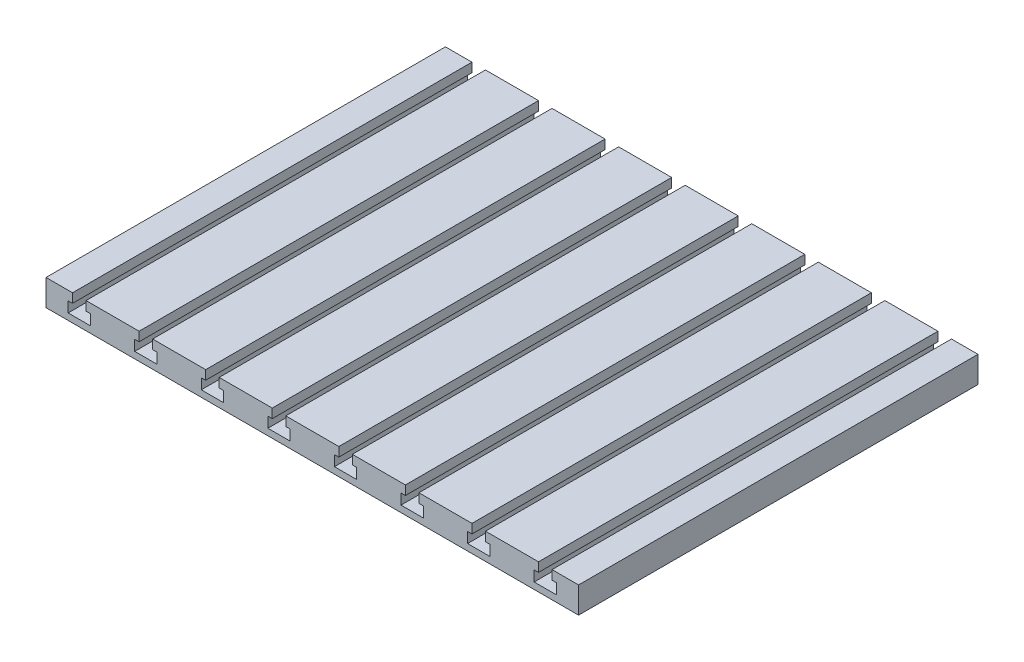
SolidWorks part; units mm, degrees
ref_plane "Front Plane" through (0, 0, 0) normal (0, 0, 1) x (1, 0, 0)
ref_plane "Top Plane" through (0, 0, 0) normal (0, 1, 0) x (1, 0, 0)
ref_plane "Right Plane" through (0, 0, 0) normal (1, 0, 0) x (0, 0, -1)
sketch "Sketch1" plane through (0, 0, 0) normal (0, 0, 1) x (1, 0, 0)
  line L0 (30.5562, 12.9794) -> (33.8963, 12.9794)
  line L1 (0, 0) -> (406.4, 0)
  line L2 (0, 0) -> (0, 19.9898)
  line L3 (0, 19.9898) -> (20.2438, 19.9898)
  line L4 (406.4, 0) -> (406.4, 19.9898)
  line L6 (20.2438, 19.9898) -> (20.2438, 12.9794)
  line L8 (30.5562, 19.9898) -> (30.5562, 12.9794)
  line L9 (16.9037, 12.9794) -> (20.2438, 12.9794)
  line L10 (16.9037, 12.9794) -> (16.9037, 4.9784)
  line L11 (16.9037, 4.9784) -> (33.8963, 4.9784)
  line L12 (33.8963, 12.9794) -> (33.8963, 4.9784)
  line L13 (25.4, 4.9784) -> (25.4, 25.0145) construction
  line L14 (71.0438, 19.9898) -> (71.0438, 12.9794)
  line L15 (67.7037, 12.9794) -> (71.0438, 12.9794)
  line L16 (67.7037, 12.9794) -> (67.7037, 4.9784)
  line L17 (67.7037, 4.9784) -> (84.6963, 4.9784)
  line L18 (84.6963, 12.9794) -> (84.6963, 4.9784)
  line L19 (81.3562, 12.9794) -> (84.6963, 12.9794)
  line L20 (81.3562, 19.9898) -> (81.3562, 12.9794)
  line L22 (121.8438, 19.9898) -> (121.8438, 12.9794)
  line L23 (118.5037, 12.9794) -> (121.8438, 12.9794)
  line L24 (118.5037, 12.9794) -> (118.5037, 4.9784)
  line L25 (118.5037, 4.9784) -> (135.4963, 4.9784)
  line L26 (135.4963, 12.9794) -> (135.4963, 4.9784)
  line L27 (132.1562, 12.9794) -> (135.4963, 12.9794)
  line L28 (132.1562, 19.9898) -> (132.1562, 12.9794)
  line L30 (172.6438, 19.9898) -> (172.6438, 12.9794)
  line L31 (169.3037, 12.9794) -> (172.6438, 12.9794)
  line L32 (169.3037, 12.9794) -> (169.3037, 4.9784)
  line L33 (169.3037, 4.9784) -> (186.2963, 4.9784)
  line L34 (186.2963, 12.9794) -> (186.2963, 4.9784)
  line L35 (182.9562, 12.9794) -> (186.2963, 12.9794)
  line L36 (182.9562, 19.9898) -> (182.9562, 12.9794)
  line L38 (223.4438, 19.9898) -> (223.4438, 12.9794)
  line L39 (220.1037, 12.9794) -> (223.4438, 12.9794)
  line L40 (220.1037, 12.9794) -> (220.1037, 4.9784)
  line L41 (220.1037, 4.9784) -> (237.0963, 4.9784)
  line L42 (237.0963, 12.9794) -> (237.0963, 4.9784)
  line L43 (233.7562, 12.9794) -> (237.0963, 12.9794)
  line L44 (233.7562, 19.9898) -> (233.7562, 12.9794)
  line L46 (274.2438, 19.9898) -> (274.2438, 12.9794)
  line L47 (270.9037, 12.9794) -> (274.2438, 12.9794)
  line L48 (270.9037, 12.9794) -> (270.9037, 4.9784)
  line L49 (270.9037, 4.9784) -> (287.8963, 4.9784)
  line L50 (287.8963, 12.9794) -> (287.8963, 4.9784)
  line L51 (284.5562, 12.9794) -> (287.8963, 12.9794)
  line L52 (284.5562, 19.9898) -> (284.5562, 12.9794)
  line L54 (30.5562, 19.9898) -> (71.0438, 19.9898)
  line L55 (81.3562, 19.9898) -> (121.8438, 19.9898)
  line L56 (132.1562, 19.9898) -> (172.6438, 19.9898)
  line L57 (182.9562, 19.9898) -> (223.4438, 19.9898)
  line L58 (233.7562, 19.9898) -> (274.2438, 19.9898)
  line L59 (284.5562, 19.9898) -> (325.0438, 19.9898)
  line L60 (321.7037, 4.9784) -> (338.6963, 4.9784)
  line L61 (321.7037, 12.9794) -> (321.7037, 4.9784)
  line L62 (325.0438, 19.9898) -> (325.0438, 12.9794)
  line L63 (321.7037, 12.9794) -> (325.0438, 12.9794)
  line L64 (335.3562, 19.9898) -> (335.3562, 12.9794)
  line L65 (335.3562, 12.9794) -> (338.6963, 12.9794)
  line L66 (338.6963, 12.9794) -> (338.6963, 4.9784)
  line L67 (372.5037, 4.9784) -> (389.4963, 4.9784)
  line L68 (372.5037, 12.9794) -> (372.5037, 4.9784)
  line L69 (375.8438, 19.9898) -> (375.8438, 12.9794)
  line L70 (372.5037, 12.9794) -> (375.8438, 12.9794)
  line L71 (386.1562, 19.9898) -> (386.1562, 12.9794)
  line L72 (386.1562, 12.9794) -> (389.4963, 12.9794)
  line L73 (389.4963, 12.9794) -> (389.4963, 4.9784)
  line L74 (335.3562, 19.9898) -> (375.8438, 19.9898)
  line L75 (386.1562, 19.9898) -> (406.4, 19.9898)
  dimension "D1" = 406.4
  dimension "D2" = 10.3124
  dimension "D3" = 7.0104
  dimension "D4" = 16.9926
  dimension "D5" = 8.001
  dimension "D6" = 25.4
  dimension "D7" = 19.9898
  dimension "D8" = 6
  dimension "D9" = 3
extrude "Boss-Extrude1" add sketch "Sketch1" along normal blind 304.8
